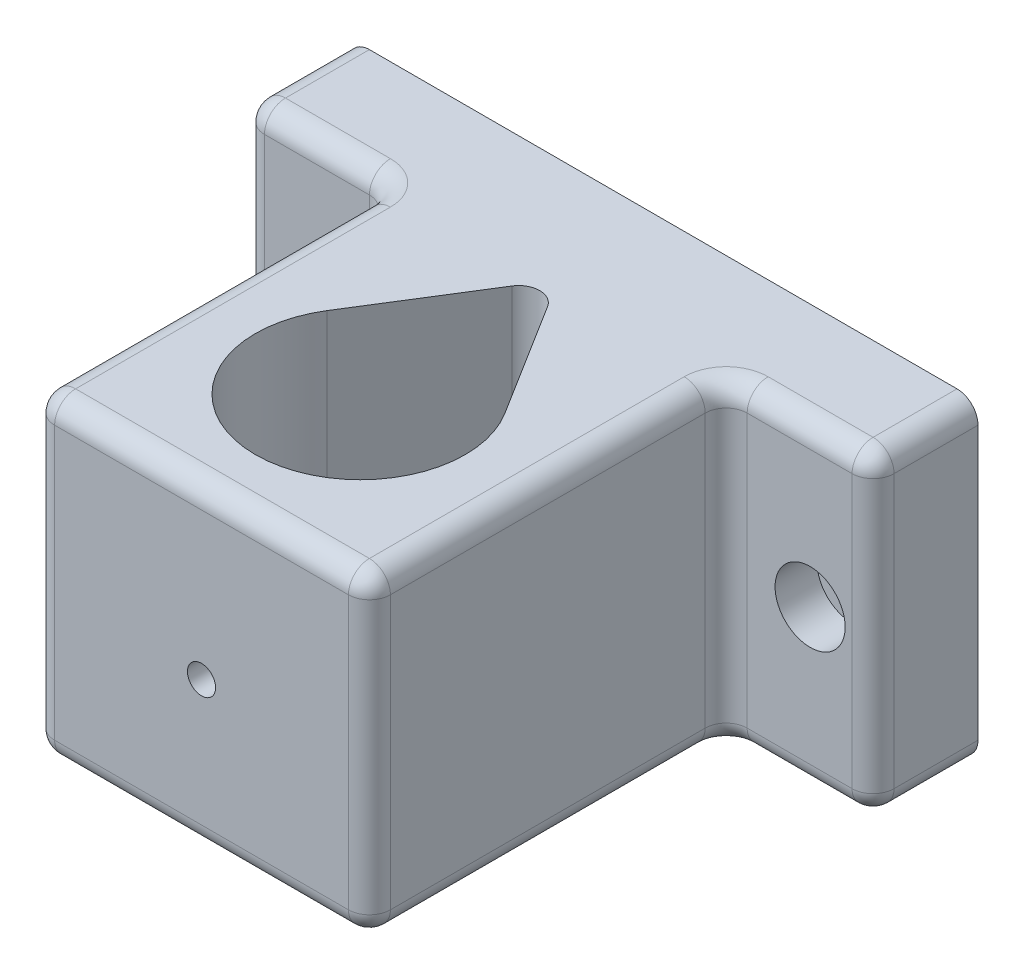
SolidWorks part; units mm, degrees
ref_plane "Front Plane" through (0, 0, 0) normal (0, 0, 1) x (1, 0, 0)
ref_plane "Top Plane" through (0, 0, 0) normal (0, 1, 0) x (1, 0, 0)
ref_plane "Right Plane" through (0, 0, 0) normal (1, 0, 0) x (0, 0, -1)
sketch "Sketch1" plane through (0, 0, 0) normal (0, 0, 1) x (1, 0, 0)
  line L1 (0, 0) -> (38.1, 0)
  line L2 (0, 0) -> (0, 19.05)
  line L3 (0, 19.05) -> (38.1, 19.05)
  line L4 (38.1, 0) -> (38.1, 19.05)
  dimension "D1" = 19.05
  dimension "D2" = 38.1
extrude "Boss-Extrude1" add sketch "Sketch1" along normal blind 27.94
sketch "Sketch2" plane through (0, 0, 27.94) normal (0, 0, 1) x (1, 0, 0)
  line L0 (0, 0) -> (38.1, 0) construction
  line L1 (0, 19.05) -> (8.89, 19.05)
  line L2 (0, 19.05) -> (0, 0)
  line L3 (0, 0) -> (8.89, 0)
  line L4 (8.89, 19.05) -> (8.89, 0)
  line L6 (38.1, 19.05) -> (29.21, 19.05)
  line L7 (38.1, 19.05) -> (38.1, 0)
  line L8 (38.1, 0) -> (29.21, 0)
  line L9 (29.21, 19.05) -> (29.21, 0)
  dimension "D1" = 8.89
  dimension "D2" = 8.89
extrude "Cut-Extrude1" cut sketch "Sketch2" against normal blind 21.59
sketch "Sketch3" plane through (0, 19.05, 0) normal (0, 1, 0) x (1, 0, 0)
  line L0 (19.05, 0) -> (19.05, -27.94) construction
  line L1 (38.1, 0) -> (0, 0) construction
  line L2 (29.21, -27.94) -> (8.89, -27.94) construction
sketch "Sketch4" plane through (0, 19.05, 0) normal (0, 1, 0) x (1, 0, 0)
  line L0 (13.6652, -14.9657) -> (19.05, -6.35)
  line L1 (19.05, -6.35) -> (24.4348, -14.9657)
  line L4 (19.05, 0) -> (19.05, -27.94) construction
  arc A1 (24.4348, -14.9657) -> (13.6652, -14.9657) centre (19.05, -18.3312) cw
  dimension "D1" = 6.35
  dimension "D2" = 6.35
  dimension "D3" = 10.16
extrude "Cut-Extrude2" cut sketch "Sketch4" against normal blind 31.75
hole_wizard "#43 (0.089) Diameter Hole1" positions "Sketch6" profile "Sketch5" hole size "#43" standard "ANSI Inch" end condition through all
sketch "Sketch6" plane through (0, 0, 6.35) normal (0, 0, 1) x (1, 0, 0)
  line L0 (8.89, 19.05) -> (0, 19.05) construction
  line L1 (38.1, 19.05) -> (29.21, 19.05) construction
  line L2 (0, 19.05) -> (0, 0) construction
  line L3 (38.1, 0) -> (38.1, 19.05) construction
  point P0 (3.81, 9.525)
  point P2 (34.29, 9.525)
  point P7 (33.655, 19.05)
  dimension "D1" = 9.525
  dimension "D2" = 9.525
  dimension "D3" = 3.81
  dimension "D4" = 3.81
sketch "Sketch5" plane through (3.81, 9.525, 6.35) normal (1, 0, 0) x (0, -1, 0)
  line L0 (0, 0) -> (0, 6.35)
  line L1 (0, 6.35) -> (1.1303, 6.35)
  line L2 (1.1303, 6.35) -> (1.1303, 0)
  line L5 (1.1303, 0) -> (0, 0)
  line L11 (0, -6.35) -> (0, 107.95) construction
  dimension "Thru Hole Dia." = 2.2606
  dimension "Thru Hole Depth" = 6.35
hole_wizard "#51 (0.067) Diameter Hole1" positions "Sketch10" profile "Sketch9" hole size "#51" standard "ANSI Inch"
sketch "Sketch10" plane through (0, 0, 27.94) normal (0, 0, 1) x (1, 0, 0)
  line L0 (29.21, 19.05) -> (29.21, 0) construction
  line L2 (29.21, 19.05) -> (8.89, 19.05) construction
  point P0 (19.05, 8.89)
  dimension "D1" = 10.16
  dimension "D2" = 10.16
sketch "Sketch9" plane through (19.05, 8.89, 27.94) normal (1, 0, 0) x (0, -1, 0)
  line L0 (0, 0) -> (0, 3.2588)
  line L1 (0, 3.2588) -> (0.8509, 3.2588)
  line L2 (0.8509, 3.2588) -> (0.8509, 0)
  line L5 (0.8509, 0) -> (0, 0)
  line L11 (0, -6.35) -> (0, 107.95) construction
  dimension "Thru Hole Dia." = 1.7018
  dimension "Thru Hole Depth" = 3.2588
fillet "Fillet1" radius 1.27 21 edges at (19.05, 9.525, 6.35) (4.445, 19.05, 6.35) (33.655, 19.05, 6.35) (8.89, 19.05, 17.145) (19.05, 19.05, 27.94) (29.21, 19.05, 17.145) (8.89, 9.525, 27.94) (29.21, 9.525, 27.94) (29.21, 9.525, 6.35) (8.89, 9.525, 6.35) (38.1, 0, 3.175) (33.655, 0, 6.35) (4.445, 0, 6.35) (0, 0, 3.175) (38.1, 19.05, 3.175) (0, 19.05, 3.175) (29.21, 0, 17.145) (8.89, 0, 17.145) (19.05, 0, 27.94) (38.1, 9.525, 6.35) (0, 9.525, 6.35)
sketch "Sketch11" plane through (0, 0, 0) normal (0, 0, -1) x (-1, 0, 0)
  line L0 (-19.05, 19.05) -> (-19.05, 0) construction
  line L1 (-36.83, 19.05) -> (-1.27, 19.05) construction
  line L2 (-1.27, 0) -> (-36.83, 0) construction
  line L3 (-38.1, 9.525) -> (0, 9.525) construction
  line L4 (-38.1, 1.27) -> (-38.1, 17.78) construction
  line L5 (0, 17.78) -> (0, 1.27) construction
  circle A0 centre (-19.05, 9.525) radius 2.75
  dimension "D1" = 5.5
extrude "Cut-Extrude3" cut sketch "Sketch11" against normal blind 2
sketch "Sketch12" plane through (0, 0, 6.35) normal (0, 0, 1) x (1, 0, 0)
  circle A0 centre (3.81, 9.525) radius 2.159
  circle A1 centre (34.29, 9.525) radius 2.1209
  dimension "D1" = 4.318
  dimension "D2" = 4.2418
extrude "Cut-Extrude4" cut sketch "Sketch12" against normal blind 2.54
